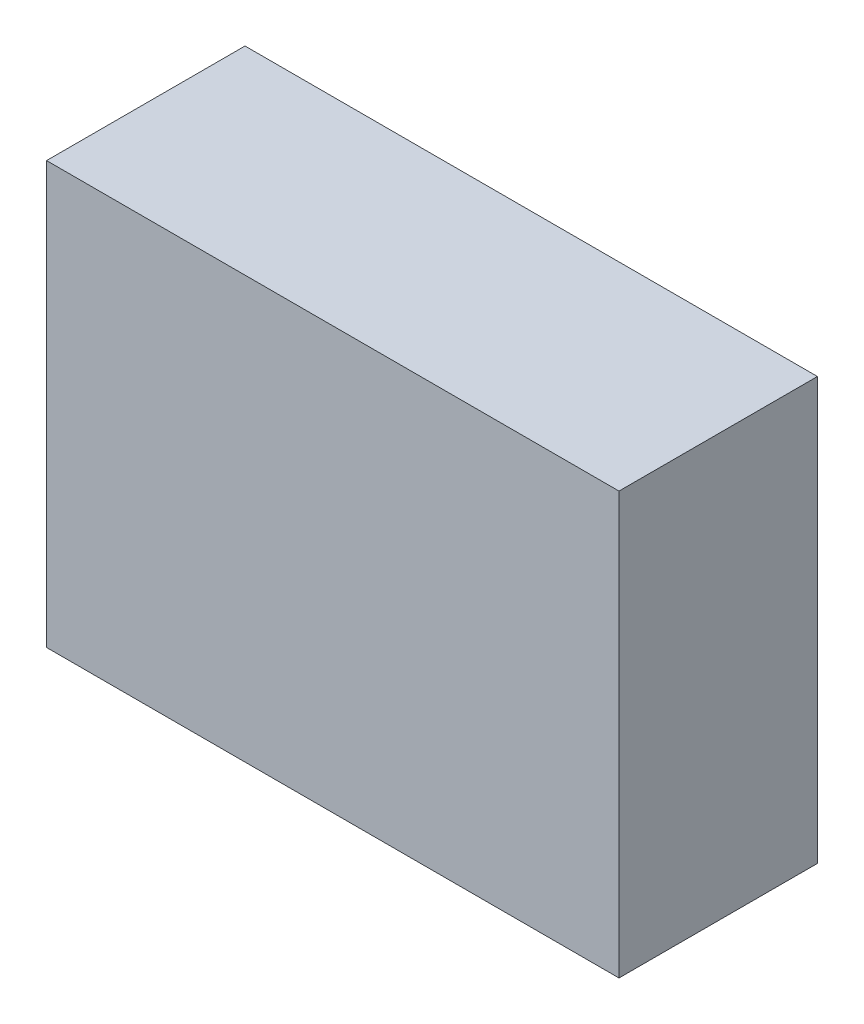
SolidWorks part; units mm, degrees
ref_plane "Front Plane" through (0, 0, 0) normal (0, 0, 1) x (1, 0, 0)
ref_plane "Top Plane" through (0, 0, 0) normal (0, 1, 0) x (1, 0, 0)
ref_plane "Right Plane" through (0, 0, 0) normal (1, 0, 0) x (0, 0, -1)
sketch "Sketch1" plane through (0, 0, 0) normal (0, 0, 1) x (1, 0, 0)
  line L0 (-1.5616, -5.0556) -> (11.8516, -5.0556)
  line L1 (11.8516, -5.0556) -> (11.8516, 4.826)
  line L2 (11.8516, 4.826) -> (-1.5616, 4.826)
  line L3 (-1.5616, 4.826) -> (-1.5616, -5.0556)
extrude "Component_Outline" add sketch "Sketch1" along normal blind 4.65 separate body
sketch3d "3DSketch1"
  line L0 (0, 0, 0) -> (1, 0, 0)
  line L1 (0, 0, 0) -> (0, 1, 0)
  line L2 (0, 0, 0) -> (0, 0, 1)
  point P0 (0, 0, 0)
